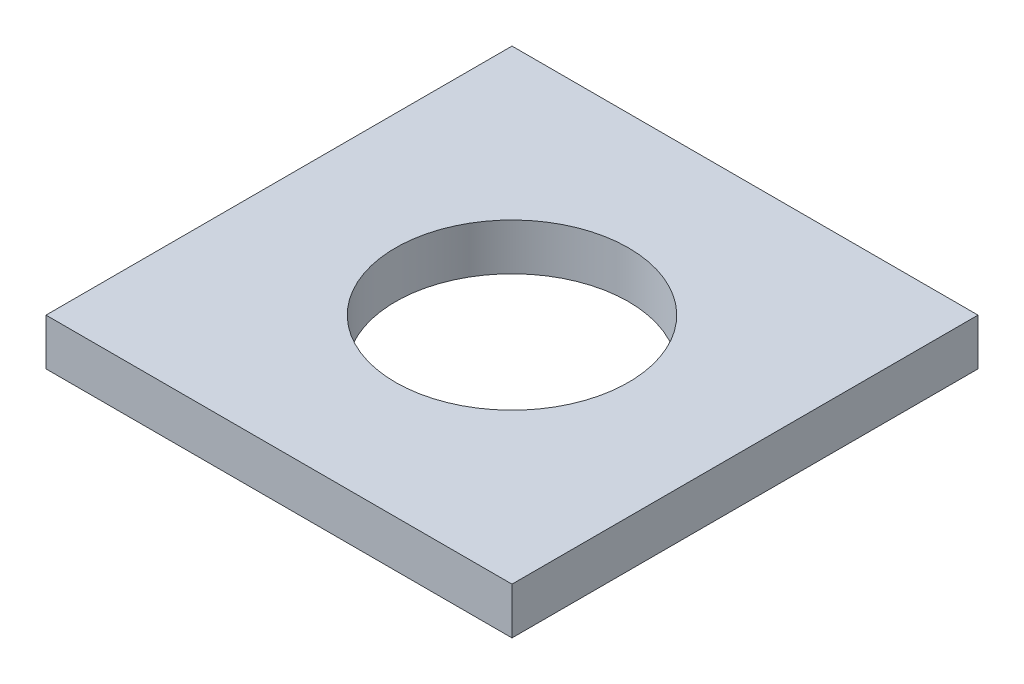
SolidWorks part; units mm, degrees
ref_plane "Front Plane" through (0, 0, 0) normal (0, 0, 1) x (1, 0, 0)
ref_plane "Top Plane" through (0, 0, 0) normal (0, 1, 0) x (1, 0, 0)
ref_plane "Right Plane" through (0, 0, 0) normal (1, 0, 0) x (0, 0, -1)
sketch "Sketch1" plane through (0, 0, 0) normal (0, 1, 0) x (1, 0, 0)
  line L1 (-4, -4) -> (4, -4)
  line L2 (-4, -4) -> (-4, 4)
  line L3 (-4, 4) -> (4, 4)
  line L4 (4, -4) -> (4, 4)
  line L5 (-4, -4) -> (4, 4) construction
  line L6 (-4, 4) -> (4, -4) construction
  circle A0 centre (0, 0) radius 2
  point P0 (0, 0)
  dimension "D1" = 4
  dimension "D2" = 8
extrude "Boss-Extrude1" add sketch "Sketch1" along normal blind 0.8
